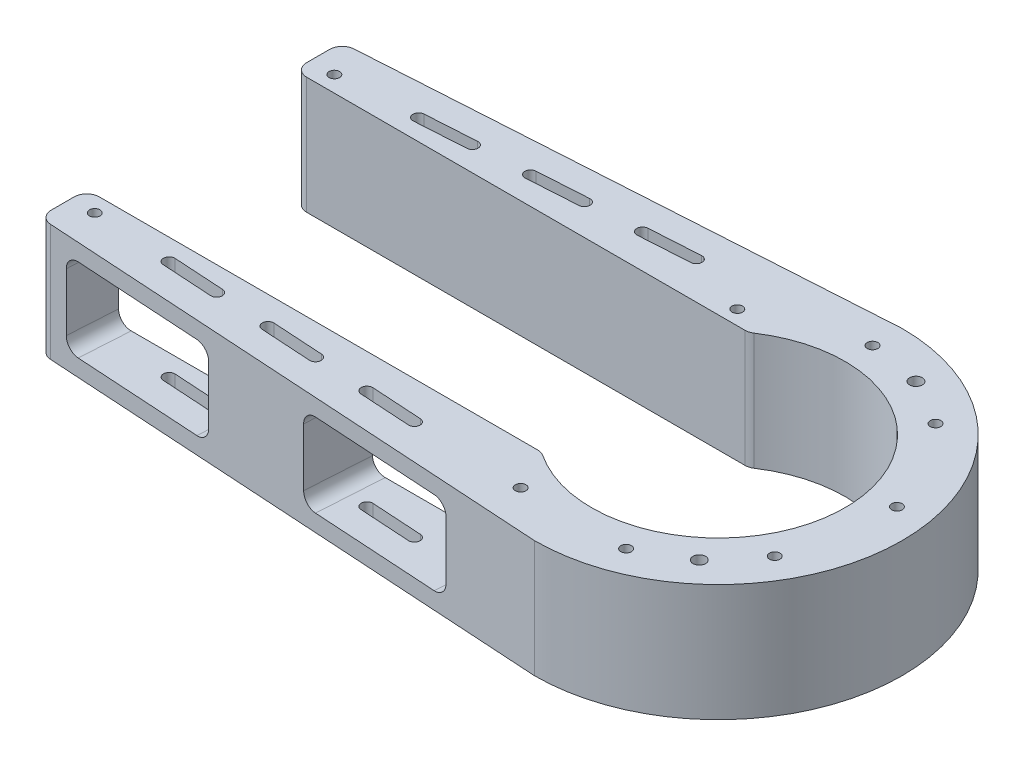
SolidWorks part; units mm, degrees
material "6061 合金"
ref_plane "前视基准面" through (0, 0, 0) normal (0, 0, 1) x (1, 0, 0)
ref_plane "上视基准面" through (0, 0, 0) normal (0, 1, 0) x (1, 0, 0)
ref_plane "右视基准面" through (0, 0, 0) normal (1, 0, 0) x (0, 0, -1)
other "Configuration Table"
sketch "草图1" plane through (0, 0, 0) normal (0, 1, 0) x (1, 0, 0)
  line L0 (0, -43.5) -> (0, 43.5) construction
  line L1 (0, 0) -> (-27.9613, 33.3229) construction
  line L2 (0, 0) -> (27.9613, 33.3229) construction
  line L3 (0, 0) -> (14.8779, 40.8766) construction
  line L4 (0, 0) -> (-250, 0) construction
  line L5 (-230.201, -19.799) -> (-269.799, 19.799) construction
  line L6 (-269.799, -19.799) -> (-230.201, 19.799) construction
  line L7 (0, 28) -> (-250, 28) construction
  line L8 (0, 28) -> (0, -28) construction
  line L9 (0, -28) -> (-250, -28) construction
  line L10 (-250, 28) -> (-250, -28) construction
  line L11 (-125, -28) -> (-125, 28) construction
  line L12 (0, 0) -> (-250, 0) construction
  line L13 (-250, 0) -> (-250, 18.6396) construction
  line L14 (-250, 0) -> (-236.565, 13.435) construction
  line L15 (-250, 0) -> (-263.435, 13.435) construction
  line L16 (-250, 28) -> (0, 43.5) construction
  line L17 (-250, -28) -> (0, -43.5) construction
  circle A0 centre (0, 0) radius 43.5 construction
  circle A1 centre (0, 0) radius 36.5 construction
  circle A2 centre (0, 0) radius 30 construction
  circle A7 centre (-23.4617, 27.9606) radius 1.25 construction
  circle A8 centre (0, 36.5) radius 1.25 construction
  circle A9 centre (12.4837, 34.2988) radius 1.5 construction
  circle A10 centre (23.4617, 27.9606) radius 1.25 construction
  circle A11 centre (35.9455, 6.3382) radius 1.25 construction
  circle A12 centre (31.6099, -18.25) radius 1.25 construction
  circle A13 centre (23.4617, -27.9606) radius 1.5 construction
  circle A14 centre (12.4837, -34.2988) radius 1.25 construction
  circle A15 centre (-12.4837, -34.2988) radius 1.25 construction
  circle A16 centre (-31.6099, -18.25) radius 1.25 construction
  circle A17 centre (-35.9455, -6.3382) radius 1.5 construction
  circle A18 centre (-35.9455, 6.3382) radius 1.25 construction
  circle A19 centre (-250, 0) radius 28 construction
  circle A20 centre (-250, 0) radius 22 construction
  circle A21 centre (-250, 0) radius 16 construction
  arc A22 (-263.435, 13.435) -> (-236.565, 13.435) centre (-250, 0) cw construction
  arc A23 (-234.4463, 15.5537) -> (-265.5537, 15.5537) centre (-250, 0) ccw construction
  arc A24 (-238.6836, 11.3164) -> (-261.3164, 11.3164) centre (-250, 0) ccw construction
  arc A25 (-238.6836, 11.3164) -> (-234.4463, 15.5537) centre (-236.565, 13.435) ccw construction
  arc A26 (-265.5537, 15.5537) -> (-261.3164, 11.3164) centre (-263.435, 13.435) ccw construction
  circle A27 centre (-250, 0) radius 4 construction
  circle A28 centre (-250, 4) radius 1.25 construction
  circle A29 centre (-254, 0) radius 1.25 construction
  circle A30 centre (-250, -4) radius 1.25 construction
  circle A31 centre (-246, 0) radius 1.25 construction
  arc A32 (-263.435, -13.435) -> (-236.565, -13.435) centre (-250, 0) ccw construction
  arc A33 (-234.4463, -15.5537) -> (-265.5537, -15.5537) centre (-250, 0) cw construction
  arc A34 (-238.6836, -11.3164) -> (-261.3164, -11.3164) centre (-250, 0) cw construction
  arc A35 (-238.6836, -11.3164) -> (-234.4463, -15.5537) centre (-236.565, -13.435) cw construction
  arc A36 (-265.5537, -15.5537) -> (-261.3164, -11.3164) centre (-263.435, -13.435) cw construction
  point P8 (0, 0)
  point P24 (-125, 0)
  point P42 (0, 0)
  point P44 (-250, 0)
  point P53 (-250, 19)
  point P71 (-250, -19)
  dimension "D1" = 3
ref_plane "基准面1" through (0, 5, 0) normal (0, 1, 0) x (1, 0, 0)
sketch "草图2" plane through (0, 5, 0) normal (0, 1, 0) x (1, 0, 0)
  line L0 (-250, 28) -> (0, 43.5)
  line L1 (-250, -28) -> (0, -43.5)
  arc A0 (-250, 28) -> (-250, -28) centre (-250, 0) ccw
  arc A1 (0, 43.5) -> (0, -43.5) centre (0, 0) cw
extrude "凸台-拉伸1" add sketch "草图2" along normal blind 27.7
sketch3d "3D草图1"
  point P0 (-145.9567, 32.7, -3.4646)
ref_plane "基准面2" through (0, 32.7, 0) normal (0, 1, 0) x (1, 0, 0)
sketch "草图3" plane through (0, 32.7, 0) normal (0, 1, 0) x (1, 0, 0)
  circle A0 centre (-250, 4) radius 1.25
  circle A1 centre (-246, 0) radius 1.25
  circle A2 centre (-250, -4) radius 1.25
  circle A3 centre (-254, 0) radius 1.25
  circle A4 centre (0, 0) radius 30
  circle A5 centre (0, 36.5) radius 1.25
  circle A6 centre (12.4837, 34.2988) radius 1.5
  circle A7 centre (23.4617, 27.9606) radius 1.25
  circle A8 centre (-23.4617, 27.9606) radius 1.25
  circle A9 centre (-35.9455, 6.3382) radius 1.25
  circle A10 centre (-35.9455, -6.3382) radius 1.5
  circle A11 centre (-31.6099, -18.25) radius 1.25
  circle A12 centre (-12.4837, -34.2988) radius 1.25
  circle A13 centre (12.4837, -34.2988) radius 1.25
  circle A14 centre (23.4617, -27.9606) radius 1.5
  circle A15 centre (31.6099, -18.25) radius 1.25
  circle A16 centre (35.9455, 6.3382) radius 1.25
  arc A17 (-265.5537, 15.5537) -> (-261.3164, 11.3164) centre (-263.435, 13.435) ccw
  arc A18 (-238.6836, 11.3164) -> (-234.4463, 15.5537) centre (-236.565, 13.435) ccw
  arc A19 (-234.4463, 15.5537) -> (-265.5537, 15.5537) centre (-250, 0) ccw
  arc A20 (-261.3164, 11.3164) -> (-238.6836, 11.3164) centre (-250, 0) cw
  arc A21 (-261.3164, -11.3164) -> (-238.6836, -11.3164) centre (-250, 0) ccw
  arc A22 (-234.4463, -15.5537) -> (-265.5537, -15.5537) centre (-250, 0) cw
  arc A23 (-265.5537, -15.5537) -> (-261.3164, -11.3164) centre (-263.435, -13.435) cw
  arc A24 (-238.6836, -11.3164) -> (-234.4463, -15.5537) centre (-236.565, -13.435) cw
extrude "切除-拉伸1" cut sketch "草图3" against normal blind 30
sketch3d "3D草图2"
  point P0 (-118.6358, 32.7, -10.1958)
ref_plane "基准面3" through (0, 32.7, 0) normal (0, 1, 0) x (1, 0, 0)
sketch "草图4" plane through (0, 32.7, 0) normal (0, 1, 0) x (1, 0, 0)
  line L0 (0, 0) -> (-250, 0) construction
  line L1 (-222.1049, 0) -> (-217.1049, 0) construction
  line L3 (-217.1049, 0) -> (-210.1249, -4.0299) construction
  line L4 (-217.1049, 0) -> (-205.2675, 20.5031) construction
  line L5 (-205.2675, 20.5031) -> (-198.2874, 16.4731) construction
  line L6 (-210.1249, -4.0299) -> (-198.2874, 16.4731) construction
  line L7 (-217.1049, 0) -> (-198.2874, 16.4731) construction
  line L8 (-205.2675, 20.5031) -> (-210.1249, -4.0299) construction
  line L28 (-214.6027, 0) -> (-194.6027, 0) construction
  line L29 (-115.7976, 0) -> (-43.3199, 0) construction
  line L30 (-216.2389, 1.5) -> (-205.2675, 20.5031)
  line L31 (-54.444, 1.5) -> (-65.7024, 21)
  line L32 (-68.3004, 22.5) -> (-90.8171, 22.5)
  line L33 (-93.4152, 21) -> (-104.6735, 1.5)
  line L34 (-104.6735, -1.5) -> (-93.4152, -21)
  line L35 (-90.8171, -22.5) -> (-68.3004, -22.5)
  line L36 (-65.7024, -21) -> (-54.444, -1.5)
  line L37 (-206.9322, 1.5) -> (-198.2874, 16.4731)
  line L38 (-206.9322, -1.5) -> (-198.2874, -16.4731)
  line L39 (-216.2389, -1.5) -> (-205.2675, -20.5031)
  line L40 (-188.9322, -1.5) -> (-180.2874, -16.4731)
  line L41 (-198.2389, -1.5) -> (-187.2675, -20.5031)
  line L42 (-198.2389, 1.5) -> (-187.2675, 20.5031)
  line L43 (-188.9322, 1.5) -> (-180.2874, 16.4731)
  line L44 (-170.9322, -1.5) -> (-162.2874, -16.4731)
  line L45 (-180.2389, -1.5) -> (-169.2675, -20.5031)
  line L46 (-180.2389, 1.5) -> (-169.2675, 20.5031)
  line L47 (-170.9322, 1.5) -> (-162.2874, 16.4731)
  line L48 (-152.9322, -1.5) -> (-144.2874, -16.4731)
  line L49 (-162.2389, -1.5) -> (-151.2675, -20.5031)
  line L50 (-162.2389, 1.5) -> (-151.2675, 20.5031)
  line L51 (-152.9322, 1.5) -> (-144.2874, 16.4731)
  line L52 (-134.9322, -1.5) -> (-126.2874, -16.4731)
  line L53 (-144.2389, -1.5) -> (-133.2675, -20.5031)
  line L54 (-144.2389, 1.5) -> (-133.2675, 20.5031)
  line L55 (-134.9322, 1.5) -> (-126.2874, 16.4731)
  line L56 (-116.9322, -1.5) -> (-108.2874, -16.4731)
  line L57 (-126.2389, -1.5) -> (-115.2675, -20.5031)
  line L58 (-126.2389, 1.5) -> (-115.2675, 20.5031)
  line L59 (-116.9322, 1.5) -> (-108.2874, 16.4731)
  line L60 (-206.9322, -1.5) -> (-188.9322, -1.5) construction
  arc A0 (-205.2675, 20.5031) -> (-198.2874, 16.4731) centre (-201.7775, 18.4881) cw construction
  circle A21 centre (-79.5588, 0) radius 22.5 construction
  arc A22 (-93.4152, 21) -> (-90.8171, 22.5) centre (-90.8171, 19.5) cw
  arc A23 (-104.6735, -1.5) -> (-104.6735, 1.5) centre (-102.0754, 0) cw
  arc A24 (-90.8171, -22.5) -> (-93.4152, -21) centre (-90.8171, -19.5) cw
  arc A25 (-65.7024, -21) -> (-68.3004, -22.5) centre (-68.3004, -19.5) cw
  arc A26 (-54.444, 1.5) -> (-54.444, -1.5) centre (-57.0421, 0) cw
  arc A27 (-65.7024, 21) -> (-68.3004, 22.5) centre (-68.3004, 19.5) ccw
  arc A28 (-205.2675, 20.5031) -> (-198.2874, 16.4731) centre (-201.7775, 18.4881) cw
  arc A29 (-205.2675, -20.5031) -> (-198.2874, -16.4731) centre (-201.7775, -18.4881) ccw
  arc A30 (-216.2389, -1.5) -> (-216.2389, 1.5) centre (-213.6408, 0) cw
  arc A31 (-206.9322, -1.5) -> (-206.9322, 1.5) centre (-204.3341, 0) cw
  arc A32 (-188.9322, -1.5) -> (-188.9322, 1.5) centre (-186.3341, 0) cw
  arc A33 (-187.2675, -20.5031) -> (-180.2874, -16.4731) centre (-183.7775, -18.4881) ccw
  arc A34 (-198.2389, -1.5) -> (-198.2389, 1.5) centre (-195.6408, 0) cw
  arc A35 (-187.2675, 20.5031) -> (-180.2874, 16.4731) centre (-183.7775, 18.4881) cw
  arc A36 (-170.9322, -1.5) -> (-170.9322, 1.5) centre (-168.3341, 0) cw
  arc A37 (-169.2675, -20.5031) -> (-162.2874, -16.4731) centre (-165.7775, -18.4881) ccw
  arc A38 (-180.2389, -1.5) -> (-180.2389, 1.5) centre (-177.6408, 0) cw
  arc A39 (-169.2675, 20.5031) -> (-162.2874, 16.4731) centre (-165.7775, 18.4881) cw
  arc A40 (-152.9322, -1.5) -> (-152.9322, 1.5) centre (-150.3341, 0) cw
  arc A41 (-151.2675, -20.5031) -> (-144.2874, -16.4731) centre (-147.7775, -18.4881) ccw
  arc A42 (-162.2389, -1.5) -> (-162.2389, 1.5) centre (-159.6408, 0) cw
  arc A43 (-151.2675, 20.5031) -> (-144.2874, 16.4731) centre (-147.7775, 18.4881) cw
  arc A44 (-134.9322, -1.5) -> (-134.9322, 1.5) centre (-132.3341, 0) cw
  arc A45 (-133.2675, -20.5031) -> (-126.2874, -16.4731) centre (-129.7775, -18.4881) ccw
  arc A46 (-144.2389, -1.5) -> (-144.2389, 1.5) centre (-141.6408, 0) cw
  arc A47 (-133.2675, 20.5031) -> (-126.2874, 16.4731) centre (-129.7775, 18.4881) cw
  arc A48 (-116.9322, -1.5) -> (-116.9322, 1.5) centre (-114.3341, 0) cw
  arc A49 (-115.2675, -20.5031) -> (-108.2874, -16.4731) centre (-111.7775, -18.4881) ccw
  arc A50 (-126.2389, -1.5) -> (-126.2389, 1.5) centre (-123.6408, 0) cw
  arc A51 (-115.2675, 20.5031) -> (-108.2874, 16.4731) centre (-111.7775, 18.4881) cw
  point P19 (-207.7982, 0)
  point P23 (-207.7982, 0)
  dimension "D2" = 3
  dimension "D5" = 3
  dimension "D6" = 3
  dimension "D7" = 3
  dimension "D8" = 3
  dimension "D9" = 3
  dimension "D10" = 3
  dimension "D11" = 18
  dimension "D3" = 3
  dimension "D4" = 6
extrude "切除-拉伸2" cut sketch "草图4" against normal blind 3
ref_plane "基准面4" through (0, 32.7, 0) normal (0, 1, 0) x (1, 0, 0)
sketch "草图5" plane through (0, 32.7, 0) normal (0, 1, 0) x (1, 0, 0)
  line L0 (-125, 0) -> (-43.5, 0) construction
  line L5 (-125, 28) -> (-27.1878, 34.0644) construction
  line L6 (0, 0) -> (-250, 0) construction
  line L11 (-250, 28) -> (0, 43.5) construction
  circle A3 centre (-44.9417, 32.9636) radius 1.25
  circle A4 centre (-69.7029, 31.4284) radius 1.25
  circle A7 centre (-119.2253, 28.358) radius 1.25
  circle A8 centre (-94.4641, 29.8932) radius 1.25
  circle A9 centre (0, 0) radius 43.5 construction
  circle A10 centre (-44.9417, -32.9636) radius 1.25
  circle A11 centre (-69.7029, -31.4284) radius 1.25
  circle A12 centre (-94.4641, -29.8932) radius 1.25
  circle A13 centre (-119.2253, -28.358) radius 1.25
  point P3 (-62.5299, 31.5812)
  point P4 (-62.5299, 31.5812)
extrude "切除-拉伸3" cut sketch "草图5" against normal blind 30
sketch3d "3D草图3"
  point P0 (-170.9019, 32.7, -25.8361)
ref_plane "基准面5" through (0, 32.7, 0) normal (0, 1, 0) x (1, 0, 0)
sketch "草图6" plane through (0, 32.7, 0) normal (0, 1, 0) x (1, 0, 0)
  line L1 (-281.6754, 38.6339) -> (-124.9483, 38.6339)
  line L2 (-281.6754, 38.6339) -> (-281.6754, -38.6174)
  line L3 (-281.6754, -38.6174) -> (-124.9483, -38.6174)
  line L4 (-124.9483, 38.6339) -> (-124.9483, -38.6174)
  line L5 (-281.6754, 38.6339) -> (-124.9483, -38.6174) construction
  line L6 (-281.6754, -38.6174) -> (-124.9483, 38.6339) construction
  point P4 (-203.3119, 0.0082)
extrude "切除-拉伸4" cut sketch "草图6" against normal blind 36
sketch3d "3D草图4"
  point P0 (-50.5315, 32.7, -14.5263)
ref_plane "基准面6" through (0, 32.7, 0) normal (0, 1, 0) x (1, 0, 0)
sketch "草图7" plane through (0, 32.7, 0) normal (0, 1, 0) x (1, 0, 0)
  line L0 (-111.7775, 22.518) -> (-19.8227, 22.518) construction
  line L1 (-111.7775, -22.518) -> (-37.2181, -22.518) construction
  line L2 (-125, -28) -> (-125, 28) construction
  line L3 (-125, 22.518) -> (-19.8227, 22.518) construction
  line L4 (-125, 22.518) -> (-125, -22.518) construction
  line L5 (-125, -22.518) -> (-19.8227, -22.518) construction
  line L6 (-19.8227, 22.518) -> (-19.8227, -22.518) construction
  line L7 (-125, 22.518) -> (-19.8227, -22.518) construction
  line L8 (-125, -22.518) -> (-19.8227, 22.518) construction
  line L10 (-127.5572, 24.5337) -> (-17.2655, 24.5337)
  line L11 (-127.5572, 24.5337) -> (-127.5572, -24.5337)
  line L12 (-127.5572, -24.5337) -> (-17.2655, -24.5337)
  line L13 (-17.2655, 24.5337) -> (-17.2655, -24.5337)
  line L14 (-127.5572, 24.5337) -> (-17.2655, -24.5337) construction
  line L15 (-127.5572, -24.5337) -> (-17.2655, 24.5337) construction
  circle A0 centre (0, 0) radius 30 construction
  circle A5 centre (0, 0) radius 30 construction
  point P6 (-72.4113, 0)
  point P14 (-72.4113, 0)
extrude "切除-拉伸5" cut sketch "草图7" against normal blind 36
fillet "圆角1" radius 3 1 edges at (-124.9483, 18.85, -35.7532)
ref_plane "基准面7" through (0, 32.7, 0) normal (0, 1, 0) x (1, 0, 0)
sketch "草图8" plane through (0, 32.7, 0) normal (0, 1, 0) x (1, 0, 0)
  line L0 (-119.2253, 28.358) -> (-69.7029, 31.4284) construction
  line L1 (-100.4526, 29.5219) -> (-88.4756, 30.2645) construction
  line L2 (-100.5361, 30.8694) -> (-88.5591, 31.6119)
  line L3 (-100.3691, 28.1745) -> (-88.3921, 28.9171)
  line L4 (-75.417, 29.7216) -> (-63.44, 30.4641)
  line L5 (-75.584, 32.4164) -> (-63.607, 33.159)
  line L6 (-75.5005, 31.069) -> (-63.5235, 31.8115) construction
  line L7 (-50.632, 33.9634) -> (-38.655, 34.706)
  line L8 (-50.4649, 31.2686) -> (-38.4879, 32.0112)
  line L9 (-50.5484, 32.616) -> (-38.5714, 33.3586) construction
  line L10 (0, 0) -> (-101.4347, 0) construction
  line L11 (-50.5484, -32.616) -> (-38.5714, -33.3586) construction
  line L12 (-50.632, -33.9634) -> (-38.655, -34.706)
  line L13 (-50.4649, -31.2686) -> (-38.4879, -32.0112)
  line L14 (-75.5005, -31.069) -> (-63.5235, -31.8115) construction
  line L15 (-75.584, -32.4164) -> (-63.607, -33.159)
  line L16 (-75.417, -29.7216) -> (-63.44, -30.4641)
  line L17 (-100.4526, -29.5219) -> (-88.4756, -30.2645) construction
  line L18 (-100.5361, -30.8694) -> (-88.5591, -31.6119)
  line L19 (-100.3691, -28.1745) -> (-88.3921, -28.9171)
  line L20 (-119.2253, -28.358) -> (-69.7029, -31.4284) construction
  arc A0 (-100.5361, 30.8694) -> (-100.3691, 28.1745) centre (-100.4526, 29.5219) ccw
  arc A1 (-88.3921, 28.9171) -> (-88.5591, 31.6119) centre (-88.4756, 30.2645) ccw
  arc A2 (-75.584, 32.4164) -> (-75.417, 29.7216) centre (-75.5005, 31.069) ccw
  arc A3 (-63.44, 30.4641) -> (-63.607, 33.159) centre (-63.5235, 31.8115) ccw
  arc A4 (-38.4879, 32.0112) -> (-38.655, 34.706) centre (-38.5714, 33.3586) ccw
  arc A5 (-50.632, 33.9634) -> (-50.4649, 31.2686) centre (-50.5484, 32.616) ccw
  arc A6 (-50.632, -33.9634) -> (-50.4649, -31.2686) centre (-50.5484, -32.616) cw
  arc A7 (-38.4879, -32.0112) -> (-38.655, -34.706) centre (-38.5714, -33.3586) cw
  arc A8 (-75.584, -32.4164) -> (-75.417, -29.7216) centre (-75.5005, -31.069) cw
  arc A9 (-63.44, -30.4641) -> (-63.607, -33.159) centre (-63.5235, -31.8115) cw
  arc A10 (-100.5361, -30.8694) -> (-100.3691, -28.1745) centre (-100.4526, -29.5219) cw
  arc A11 (-88.3921, -28.9171) -> (-88.5591, -31.6119) centre (-88.4756, -30.2645) cw
  point P5 (-94.4641, 29.8932)
  point P7 (-94.4641, 29.8932)
  point P15 (-69.512, 31.4403)
  point P22 (-44.5599, 32.9873)
  point P30 (-44.5599, -32.9873)
  point P37 (-69.512, -31.4403)
  point P44 (-94.4641, -29.8932)
  dimension "D1" = 2
  dimension "D2" = 2
extrude "切除-拉伸6" cut sketch "草图8" against normal blind 40
sketch3d "3D草图5"
  point P0 (-61.6107, 20.4017, 39.6801)
ref_plane "基准面8" through (-2.6867, 0, 43.3334) normal (-0.0619, 0, 0.9981) x (0.9981, 0, 0.0619)
sketch "草图9" plane through (-2.6867, 0, 43.3334) normal (-0.0619, 0, 0.9981) x (0.9981, 0, 0.0619)
  line L0 (-115.6767, 9) -> (-115.6767, 28.7) construction
  line L5 (-115.6767, 28.7) -> (-1.3082, 28.7) construction
  line L6 (-1.3082, 9) -> (-1.3082, 28.7) construction
  line L7 (-115.6767, 9) -> (-1.3082, 9) construction
  line L8 (-55.6767, 25.7) -> (-55.6767, 12)
  line L9 (-112.6767, 28.7) -> (-82.6767, 28.7)
  line L10 (-115.6767, 25.7) -> (-115.6767, 12)
  line L11 (-112.6767, 9) -> (-82.6767, 9)
  line L12 (-79.6767, 25.7) -> (-79.6767, 12)
  line L13 (-52.6767, 28.7) -> (-22.6767, 28.7)
  line L14 (-19.6767, 25.7) -> (-19.6767, 12)
  line L15 (-52.6767, 9) -> (-22.6767, 9)
  arc A0 (-82.6767, 28.7) -> (-79.6767, 25.7) centre (-82.6767, 25.7) cw
  arc A1 (-79.6767, 12) -> (-82.6767, 9) centre (-82.6767, 12) cw
  arc A2 (-112.6767, 9) -> (-115.6767, 12) centre (-112.6767, 12) cw
  arc A3 (-115.6767, 25.7) -> (-112.6767, 28.7) centre (-112.6767, 25.7) cw
  arc A4 (-55.6767, 25.7) -> (-52.6767, 28.7) centre (-52.6767, 25.7) cw
  arc A5 (-52.6767, 9) -> (-55.6767, 12) centre (-52.6767, 12) cw
  arc A6 (-22.6767, 28.7) -> (-19.6767, 25.7) centre (-22.6767, 25.7) cw
  arc A7 (-19.6767, 12) -> (-22.6767, 9) centre (-22.6767, 12) cw
  point P12 (-79.6767, 9)
  dimension "D1" = 3
  dimension "D2" = 2
extrude "切除-拉伸7" cut sketch "草图9" against normal blind 40
fillet "圆角2" radius 3 5 edges at (-124.9483, 18.85, 35.7532) (-124.9483, 18.85, 24.5337) (-17.2655, 18.85, 24.5337) (-17.2655, 18.85, -24.5337) (-124.9483, 18.85, -24.5337)
